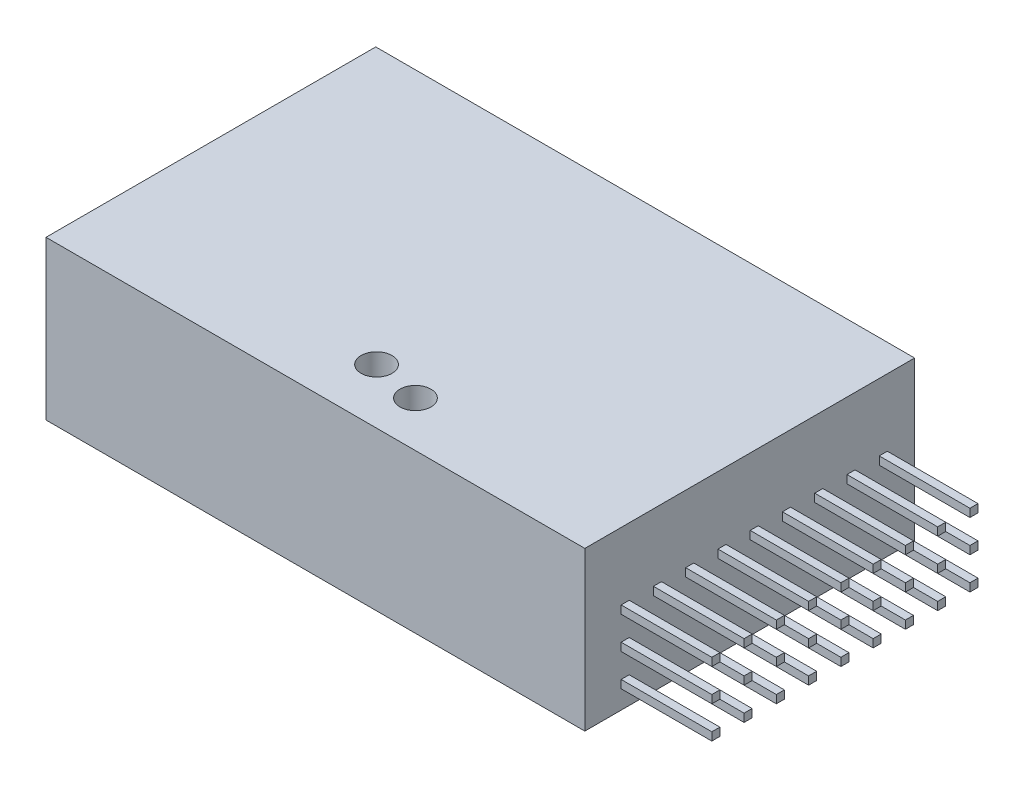
SolidWorks part; units mm, degrees
material "Delrin 2700 NC010, Low Viscosity Acetal Copolymer (SS)"
ref_plane "Front Plane" through (0, 0, 0) normal (0, 0, 1) x (1, 0, 0)
ref_plane "Top Plane" through (0, 0, 0) normal (0, 1, 0) x (1, 0, 0)
ref_plane "Right Plane" through (0, 0, 0) normal (1, 0, 0) x (0, 0, -1)
sketch "Sketch1" plane through (0, 0, 0) normal (0, 1, 0) x (1, 0, 0)
  line L1 (0, 0) -> (42.418, 0)
  line L2 (0, 0) -> (0, 25.9588)
  line L3 (0, 25.9588) -> (42.418, 25.9588)
  line L4 (42.418, 0) -> (42.418, 25.9588)
  dimension "D1" = 42.418
  dimension "D2" = 25.9588
extrude "Casing" add sketch "Sketch1" along normal blind 12.4587
sketch "Sketch2" plane through (42.418, 0, 0) normal (1, 0, 0) x (0, 0, -1)
  line L1 (23.1775, 7.1755) -> (23.8125, 7.1755)
  line L2 (23.1775, 7.1755) -> (23.1775, 6.5405)
  line L3 (23.1775, 6.5405) -> (23.8125, 6.5405)
  line L4 (23.8125, 7.1755) -> (23.8125, 6.5405)
  line L5 (23.1775, 4.6355) -> (23.8125, 4.6355)
  line L6 (23.1775, 4.6355) -> (23.1775, 4.0005)
  line L7 (23.1775, 4.0005) -> (23.8125, 4.0005)
  line L8 (23.8125, 4.6355) -> (23.8125, 4.0005)
  line L9 (23.1775, 2.0955) -> (23.8125, 2.0955)
  line L10 (23.1775, 2.0955) -> (23.1775, 1.4605)
  line L11 (23.1775, 1.4605) -> (23.8125, 1.4605)
  line L12 (23.8125, 2.0955) -> (23.8125, 1.4605)
  line L13 (0, 12.4587) -> (25.9588, 12.4587) construction
  line L14 (25.9588, 12.4587) -> (25.9588, 0) construction
  dimension "D1" = 0.635
  dimension "D2" = 1.905
  dimension "D3" = 1.905
  dimension "D4" = 5.9182
  dimension "D5" = 2.7813
extrude "Pins" add sketch "Sketch2" along normal blind 7.1374
pattern_linear "Pins pattern" count 9 spacing 2.54 along (0, 0, 1) of "Pins"
sketch "Sketch3" plane through (0, 12.4587, 0) normal (0, 1, 0) x (1, 0, 0)
  line L0 (25.5016, 4.8006) -> (34.0772, 4.8006) construction
  line L1 (26.7208, 3.5814) -> (26.7208, 0.2575) construction
  line L3 (42.418, 25.9588) -> (0, 25.9588) construction
  line L4 (42.418, 0) -> (42.418, 25.9588) construction
  circle A0 centre (25.5016, 3.5814) radius 1.2192
  dimension "D1" = 2.4384
  dimension "D2" = 21.1582
  dimension "D3" = 15.6972
extrude "LED" cut sketch "Sketch3" against normal blind 5.0673
sketch "Sketch4" plane through (0, 12.4587, 0) normal (0, 1, 0) x (1, 0, 0)
  line L0 (21.6789, 3.1242) -> (15.053, 3.1242) construction
  line L1 (22.8981, 4.3434) -> (22.8981, 10.1806) construction
  line L2 (0, 0) -> (42.418, 0) construction
  line L3 (42.418, 0) -> (42.418, 25.9588) construction
  circle A0 centre (21.6789, 4.3434) radius 1.2192
  circle A1 centre (25.5016, 3.5814) radius 1.2192 construction
  dimension "D1" = 3.1242
  dimension "D2" = 19.5199
extrude "Scan button" cut sketch "Sketch4" against normal blind 3.6195
